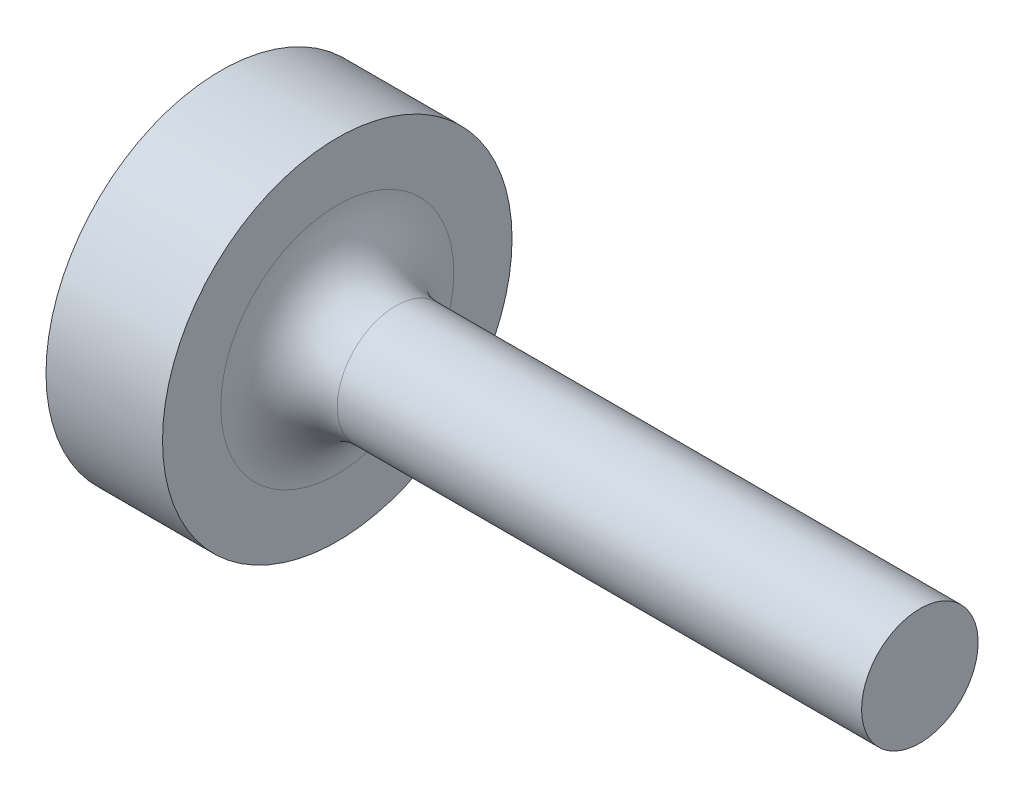
SolidWorks part; units mm, degrees
ref_plane "Front Plane" through (0, 0, 0) normal (0, 0, 1) x (1, 0, 0)
ref_plane "Top Plane" through (0, 0, 0) normal (0, 1, 0) x (1, 0, 0)
ref_plane "Right Plane" through (0, 0, 0) normal (1, 0, 0) x (0, 0, -1)
sketch "Sketch1" plane through (0, 0, 0) normal (0, 0, 1) x (1, 0, 0)
  line L0 (-2, 0) -> (10, 0)
  line L1 (10, 0) -> (10, 1)
  line L2 (10, 1) -> (1, 1)
  line L3 (0, 2) -> (0, 3)
  line L4 (0, 3) -> (-2, 3)
  line L5 (-2, 3) -> (-2, 0)
  arc A1 (1, 1) -> (0, 2) centre (1, 2) cw
  point P0 (0, 1)
  dimension "D1" = 1
  dimension "D2" = 2
  dimension "D3" = 1
  dimension "D4" = 3
  dimension "D5" = 12
revolve "Revolve1" add sketch "Sketch1" angle 360 about L0
